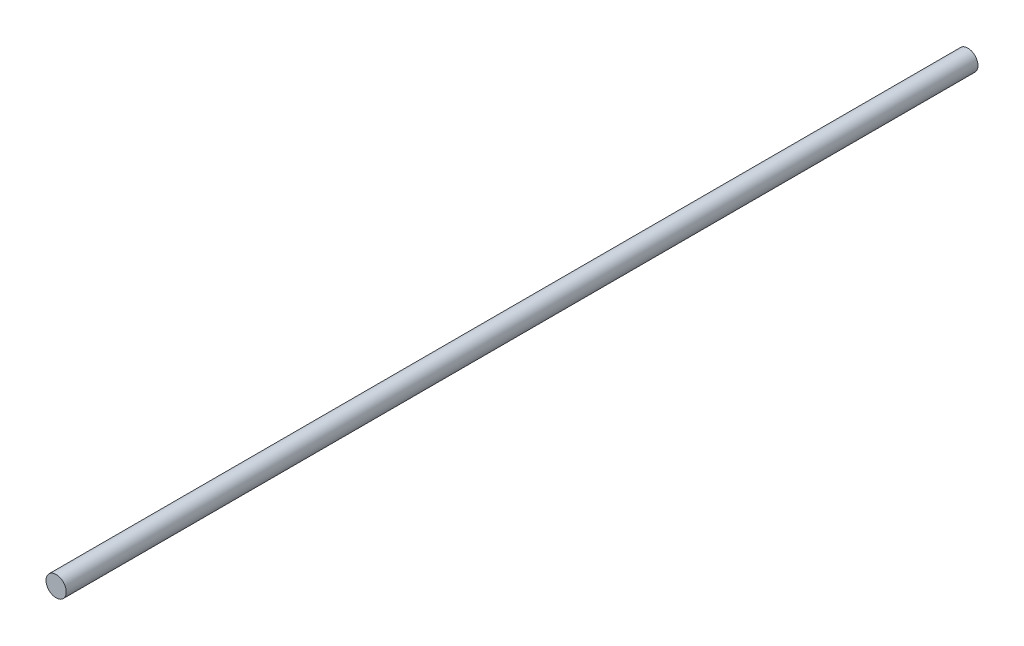
SolidWorks part; units mm, degrees
ref_plane "Front Plane" through (0, 0, 0) normal (0, 0, 1) x (1, 0, 0)
ref_plane "Top Plane" through (0, 0, 0) normal (0, 1, 0) x (1, 0, 0)
ref_plane "Right Plane" through (0, 0, 0) normal (1, 0, 0) x (0, 0, -1)
sketch "Sketch1" plane through (0, 0, 0) normal (0, 0, 1) x (1, 0, 0)
  circle A0 centre (0, 0) radius 10
  dimension "D1" = 20
extrude "Boss-Extrude1" add sketch "Sketch1" along normal blind 900
